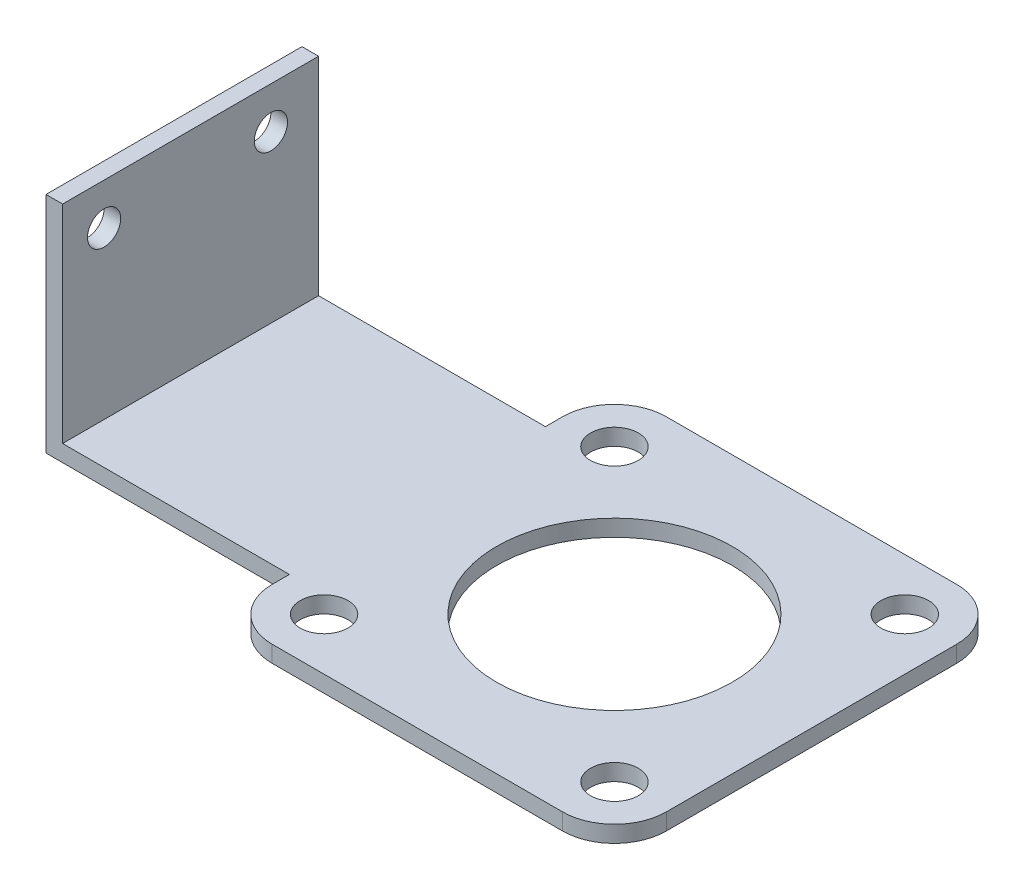
SolidWorks part; units mm, degrees
ref_plane "Front" through (0, 0, 0) normal (0, 0, 1) x (1, 0, 0)
ref_plane "Top" through (0, 0, 0) normal (0, 1, 0) x (1, 0, 0)
ref_plane "Right" through (0, 0, 0) normal (1, 0, 0) x (0, 0, -1)
sketch "Sketch1" plane through (0, 0, 0) normal (0, 1, 0) x (1, 0, 0)
  line L0 (12.5, 0) -> (82.5, 0)
  line L1 (0, 12.5) -> (0, 82.5)
  line L2 (12.5, 95) -> (82.5, 95)
  line L3 (95, 82.5) -> (95, 12.5)
  arc A0 (82.5, 95) -> (95, 82.5) centre (82.5, 82.5) cw
  arc A1 (95, 12.5) -> (82.5, 0) centre (82.5, 12.5) cw
  arc A2 (12.5, 0) -> (0, 12.5) centre (12.5, 12.5) cw
  arc A3 (12.5, 95) -> (0, 82.5) centre (12.5, 82.5) ccw
  point P9 (95, 0)
  point P12 (0, 0)
  point P15 (0, 95)
  dimension "D3" = 12.5
  dimension "D1" = 95
  dimension "D2" = 95
extrude "Boss-Extrude1" add sketch "Sketch1" along normal blind 4
sketch "Sketch2" plane through (0, 4, 0) normal (0, 1, 0) x (1, 0, 0)
  line L0 (47.5, 95) -> (47.5, 0) construction
  line L1 (82.5, 95) -> (12.5, 95) construction
  line L2 (12.5, 0) -> (82.5, 0) construction
  line L3 (12.5, 95) -> (12.5, 82.5) construction
  line L4 (0, 82.5) -> (12.5, 82.5) construction
  line L5 (95, 82.5) -> (82.5, 82.5) construction
  line L6 (82.5, 95) -> (82.5, 82.5) construction
  line L7 (0, 12.5) -> (12.5, 12.5) construction
  line L8 (95, 12.5) -> (82.5, 12.5) construction
  circle A1 centre (12.5, 82.5) radius 5.75
  circle A2 centre (82.5, 82.5) radius 5.75
  circle A3 centre (12.5, 12.5) radius 5.75
  circle A4 centre (82.5, 12.5) radius 5.75
  dimension "D3" = 11.5
  dimension "D6" = 11.5
  dimension "D7" = 11.5
  dimension "D9" = 11.5
  dimension "D2" = 12.5
  dimension "D8" = 12.5
extrude "Cut-Extrude1" cut sketch "Sketch2" against normal blind 10 and the other way blind 10
sketch "Sketch8" plane through (0, 0, 0) normal (-1, 0, 0) x (0, 0, 1)
  line L0 (-17.6413, 4) -> (-16.6413, 4)
  line L1 (-17.6413, 4) -> (-77.3587, 4)
  line L21 (-77.3587, 4) -> (-78.3587, 4)
  line L25 (-78.3587, 4) -> (-78.3587, 0)
  line L26 (-82.5, 0) -> (-12.5, 0) construction
  line L27 (-78.3587, 0) -> (-16.6413, 0)
  line L28 (-16.6413, 0) -> (-16.6413, 4)
  point P5 (-47.5, 4)
extrude "Boss-Extrude5" add sketch "Sketch8" along normal blind 58.68
sketch "Sketch12" plane through (0, 4, 0) normal (0, 1, 0) x (1, 0, 0)
  line L2 (-58.68, 78.3587) -> (-54.68, 78.3587)
  line L4 (-58.68, 78.3587) -> (0, 78.3587) construction
  line L12 (-54.68, 78.3587) -> (-54.68, 16.6413)
  line L13 (-58.68, 16.6413) -> (0, 16.6413) construction
  line L14 (-54.68, 16.6413) -> (-58.68, 16.6413)
  line L15 (-58.68, 16.6413) -> (-58.68, 78.3587)
  dimension "D1" = 4
extrude "Boss-Extrude8" add sketch "Sketch12" along normal blind 50
sketch "Sketch13" plane through (-58.68, 0, 0) normal (-1, 0, 0) x (0, 0, 1)
  line L0 (-66.8587, 44) -> (-78.3587, 44) construction
  line L1 (-78.3587, 54) -> (-78.3587, 0) construction
  line L2 (-66.8587, 44) -> (-66.8587, 54) construction
  line L3 (-78.3587, 54) -> (-16.6413, 54) construction
  line L4 (-26.6413, 54) -> (-26.6413, 44) construction
  line L5 (-26.6413, 44) -> (-16.6413, 44) construction
  line L6 (-16.6413, 0) -> (-16.6413, 54) construction
  circle A0 centre (-66.8587, 44) radius 4
  circle A1 centre (-26.6413, 44) radius 4
  dimension "D2" = 8
  dimension "D5" = 8
  dimension "D1" = 11.5
  dimension "D3" = 10
  dimension "D4" = 10
  dimension "D6" = 10
extrude "Cut-Extrude5" cut sketch "Sketch13" against normal blind 20
sketch "Sketch14" plane through (0, 4, 0) normal (0, 1, 0) x (1, 0, 0)
  line L0 (47.5, 95) -> (47.5, 0) construction
  line L1 (82.5, 95) -> (12.5, 95) construction
  line L2 (12.5, 0) -> (82.5, 0) construction
  circle A0 centre (47.5, 47.5) radius 28.395
  dimension "D1" = 56.79
extrude "Cut-Extrude6" cut sketch "Sketch14" against normal blind 10
